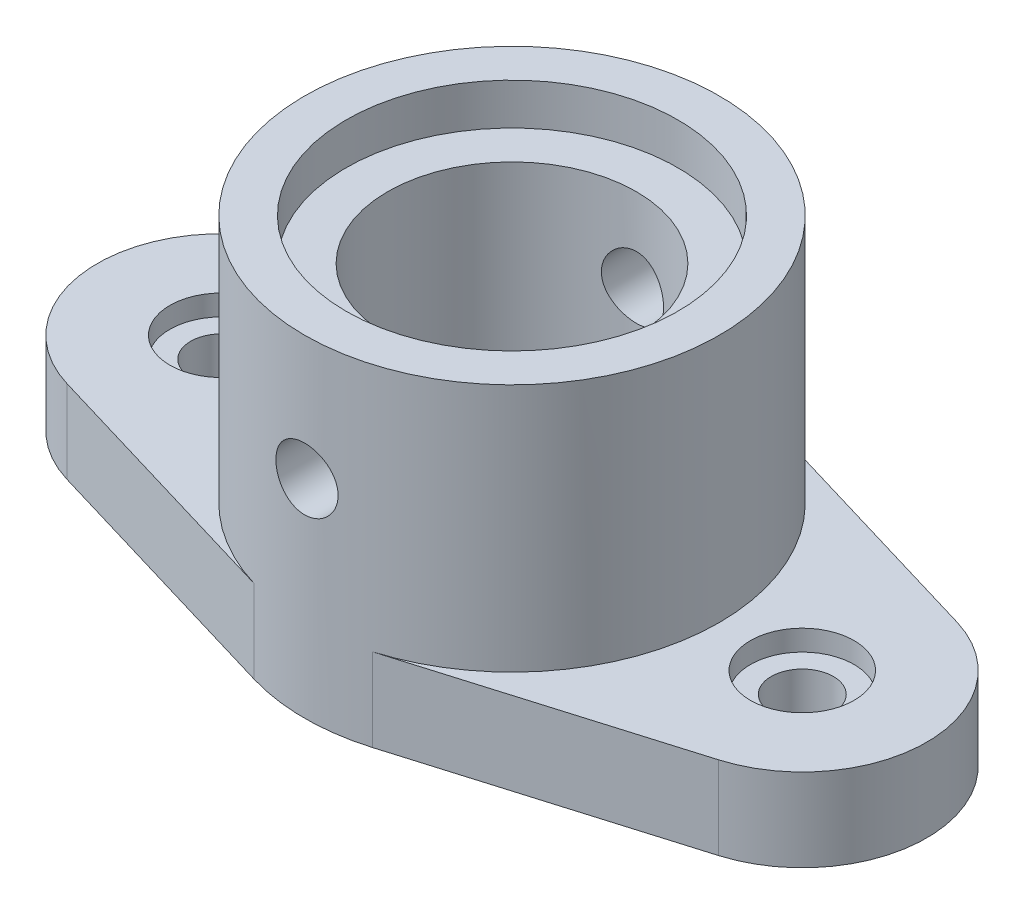
SolidWorks part; units mm, degrees
material "Gray Cast Iron"
ref_plane "Front Plane" through (0, 0, 0) normal (0, 0, 1) x (1, 0, 0)
ref_plane "Top Plane" through (0, 0, 0) normal (0, 1, 0) x (1, 0, 0)
ref_plane "Right Plane" through (0, 0, 0) normal (1, 0, 0) x (0, 0, -1)
sketch "Sketch1" plane through (0, 0, 0) normal (0, 1, 0) x (1, 0, 0)
  line L0 (-49.8929, 18.2559) -> (-9.0714, 30.4265)
  line L1 (49.8929, 18.2559) -> (9.0714, 30.4265)
  line L2 (-49.8929, -18.2559) -> (-9.0714, -30.4265)
  line L3 (49.8929, -18.2559) -> (9.0714, -30.4265)
  circle A0 centre (0, 0) radius 31.75
  arc A1 (-49.8929, 18.2559) -> (-49.8929, -18.2559) centre (-44.45, 0) ccw
  arc A2 (49.8929, -18.2559) -> (49.8929, 18.2559) centre (44.45, 0) ccw
  circle A3 centre (0, 0) radius 19.05
  dimension "D2" = 63.5
  dimension "D3" = 19.05
  dimension "D4" = 38.1
  dimension "D1" = 88.9
extrude "Boss-Extrude1" add sketch "Sketch1" along normal blind 12.7 contours L0 A1 L2 A0 | A0 A3 | L3 A2 L1 A0
sketch "Sketch2" plane through (0, 12.7, 0) normal (0, 1, 0) x (1, 0, 0)
  circle A0 centre (0, 0) radius 31.75
  circle A1 centre (0, 0) radius 19.05
  circle A2 centre (0, 0) radius 19.05 construction
  arc A3 (-9.0714, -30.4265) -> (9.0714, -30.4265) centre (0, 0) ccw construction
extrude "Boss-Extrude2" add sketch "Sketch2" along normal blind 38.1
sketch "Sketch3" plane through (0, 50.8, 0) normal (0, 1, 0) x (1, 0, 0)
  circle A0 centre (0, 0) radius 25.4
  dimension "D1" = 50.8
extrude "Cut-Extrude1" cut sketch "Sketch3" against normal blind 6.35
hole_wizard "Hole1" positions "Sketch4" profile "Sketch5" legacy end condition through all
sketch "Sketch4" plane through (0, 12.7, 0) normal (0, 1, 0) x (1, 0, 0)
  point P0 (-44.45, 0)
  point P3 (44.45, 0)
sketch "Sketch5" plane through (-44.45, 12.7, 0) normal (1, 0, 0) x (0, 0, 1)
  line L0 (0, 0) -> (0, 15.5616)
  line L1 (0, 15.5616) -> (4.7625, 12.7)
  line L2 (4.7625, 12.7) -> (4.7625, 3.175)
  line L3 (4.7625, 3.175) -> (7.9375, 3.175)
  line L4 (7.9375, 0) -> (0, 0)
  line L5 (0, -11.3109) -> (0, 121.1557) construction
  line L6 (0, 15.5616) -> (-4.7625, 12.7) construction
  line L7 (7.9375, 3.175) -> (7.9375, 0)
  dimension "Depth" = 12.7
  dimension "Drill Angle" = 118
  dimension "Diameter" = 9.525
  dimension "C-Bore Diameter" = 15.875
  dimension "C-Bore Depth" = 3.175
hole_wizard "3/8 (0.375) Diameter Hole1" positions "3DSketch2" profile "Sketch7" hole size "3/8" standard "ANSI Inch" end condition through all
sketch3d "3DSketch2"
  line L2 (0, 0, -31.75) -> (0, 31.75, -31.75) construction
  line L4 (0, 31.75, -31.75) -> (0, 0, -31.75)
  arc A0 (9.0714, 0, -30.4265) -> (-9.0714, 0, -30.4265) centre (0, 0, 0) ccw construction
  point P0 (0, 31.75, -31.75)
  point P12 (0, 31.75, 0)
  dimension "D1" = 31.75
sketch "Sketch7" plane through (0, 31.75, -31.75) normal (1, 0, 0) x (0, 1, 0)
  line L0 (0, 0) -> (0, 63.5)
  line L1 (0, 63.5) -> (4.7625, 63.5)
  line L2 (4.7625, 63.5) -> (4.7625, 0)
  line L5 (4.7625, 0) -> (0, 0)
  line L11 (0, -6.35) -> (0, 107.95) construction
  dimension "Thru Hole Dia." = 9.525
  dimension "Thru Hole Depth" = 63.5
